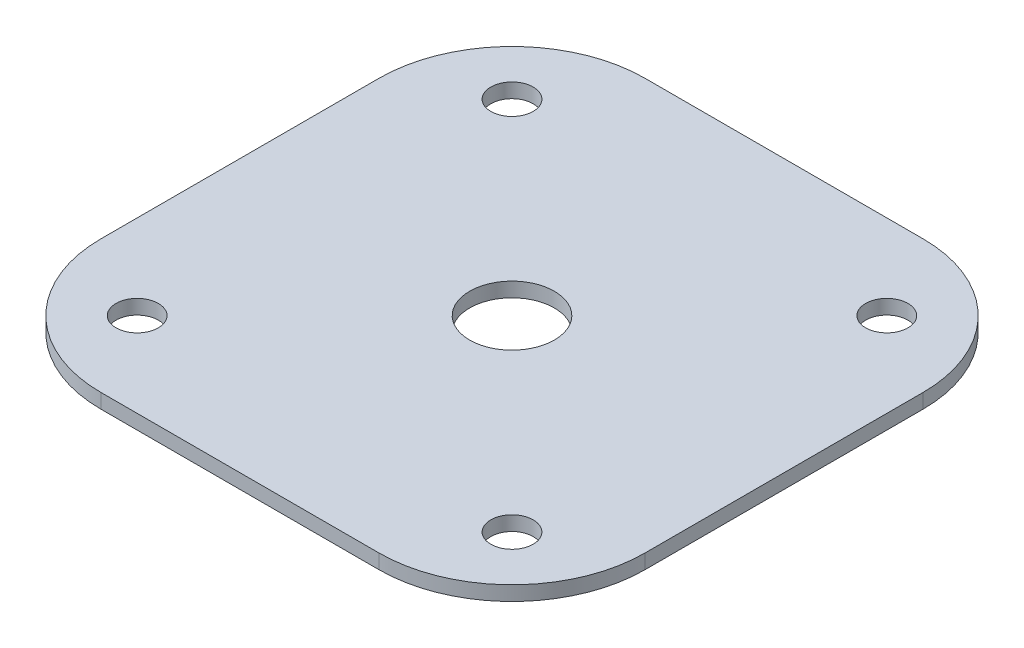
SolidWorks part; units mm, degrees
ref_plane "Front Plane" through (0, 0, 0) normal (0, 0, 1) x (1, 0, 0)
ref_plane "Top Plane" through (0, 0, 0) normal (0, 1, 0) x (1, 0, 0)
ref_plane "Right Plane" through (0, 0, 0) normal (1, 0, 0) x (0, 0, -1)
sketch "Sketch1" plane through (0, 0, 0) normal (0, 1, 0) x (1, 0, 0)
  line L0 (0, 0) -> (0, 22.5) construction
  line L1 (-11.5, 22.5) -> (11.5, 22.5)
  line L2 (-22.5, 11.5) -> (-22.5, -11.5)
  line L3 (-11.5, -22.5) -> (11.5, -22.5)
  line L4 (22.5, 11.5) -> (22.5, -11.5)
  line L5 (0, 0) -> (-22.5, 0) construction
  line L6 (0, 0) -> (-11.5, 11.5) construction
  line L7 (0, 0) -> (11.5, 11.5) construction
  circle A0 centre (0, 0) radius 3.5
  arc A1 (-22.5, -11.5) -> (-11.5, -22.5) centre (-11.5, -11.5) ccw
  arc A2 (11.5, -22.5) -> (22.5, -11.5) centre (11.5, -11.5) ccw
  arc A3 (11.5, 22.5) -> (22.5, 11.5) centre (11.5, 11.5) cw
  arc A4 (-11.5, 22.5) -> (-22.5, 11.5) centre (-11.5, 11.5) ccw
  circle A5 centre (0, 0) radius 21.9203 construction
  circle A6 centre (-15.5, 15.5) radius 1.75
  circle A7 centre (15.5, 15.5) radius 1.75
  circle A8 centre (15.5, -15.5) radius 1.75
  circle A9 centre (-15.5, -15.5) radius 1.75
  dimension "D1" = 7
  dimension "D4" = 11
  dimension "D5" = 3.5
  dimension "D6" = 31
  dimension "D2" = 45
  dimension "D3" = 45
extrude "Boss-Extrude1" add sketch "Sketch1" along normal blind 1.2
sketch "Sketch2" plane through (0, 0, 0) normal (0, 1, 0) x (1, 0, 0)
  line L0 (-22.5, 11.5) -> (-22.5, -11.5) construction
  line L3 (-12.1262, 5) -> (-44, 5)
  line L4 (-12.1262, 5) -> (-12.1262, -5)
  line L5 (-12.1262, -5) -> (-44, -5)
  line L6 (-46, 3) -> (-46, -3)
  arc A3 (-44, -5) -> (-46, -3) centre (-44, -3) cw
  arc A4 (-44, 5) -> (-46, 3) centre (-44, 3) ccw
  point P5 (-12.1262, 0)
  dimension "D2" = 2
  dimension "D1" = 10
  dimension "D3" = 23.5
extrude "Boss-Extrude2" [suppressed] add sketch "Sketch2" along normal up to surface (1.2 mm away)
fillet "Fillet1" [suppressed] radius 2
